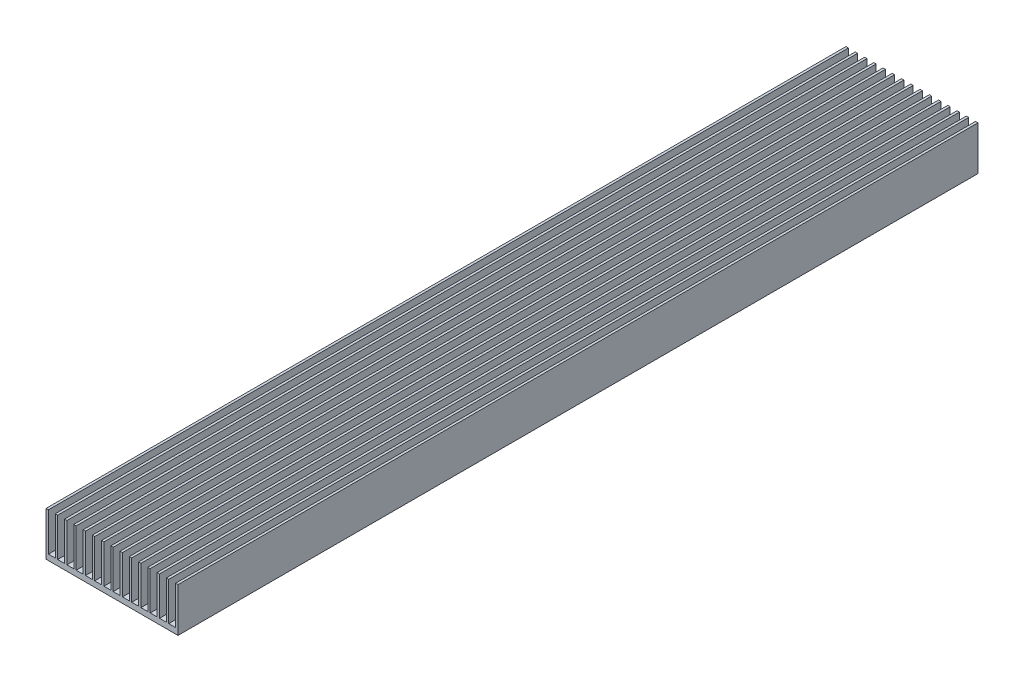
SolidWorks part; units mm, degrees
ref_plane "Ön Düzlem" through (0, 0, 0) normal (0, 0, 1) x (1, 0, 0)
ref_plane "Üst Düzlem" through (0, 0, 0) normal (0, 1, 0) x (1, 0, 0)
ref_plane "Sağ Düzlem" through (0, 0, 0) normal (1, 0, 0) x (0, 0, -1)
sketch "Sketch1" plane through (0, 0, 0) normal (0, 0, 1) x (1, 0, 0)
  line L0 (11.5714, 7) -> (11.5714, 55)
  line L1 (0, 0) -> (165, 0)
  line L2 (0, 0) -> (0, 7)
  line L3 (3, 7) -> (11.5714, 7)
  line L4 (165, 0) -> (165, 10)
  line L6 (0, 7) -> (0, 55)
  line L7 (0, 55) -> (3, 55)
  line L8 (3, 7) -> (3, 55)
  line L10 (14.5714, 7) -> (14.5714, 55)
  line L11 (11.5714, 55) -> (14.5714, 55)
  line L12 (23.1429, 7) -> (23.1429, 55)
  line L14 (26.1429, 7) -> (26.1429, 55)
  line L15 (23.1429, 55) -> (26.1429, 55)
  line L16 (34.7143, 7) -> (34.7143, 55)
  line L18 (37.7143, 7) -> (37.7143, 55)
  line L19 (34.7143, 55) -> (37.7143, 55)
  line L20 (46.2857, 7) -> (46.2857, 55)
  line L22 (49.2857, 7) -> (49.2857, 55)
  line L23 (46.2857, 55) -> (49.2857, 55)
  line L24 (57.8571, 7) -> (57.8571, 55)
  line L26 (60.8571, 7) -> (60.8571, 55)
  line L27 (57.8571, 55) -> (60.8571, 55)
  line L28 (69.4286, 7) -> (69.4286, 55)
  line L30 (72.4286, 7) -> (72.4286, 55)
  line L31 (69.4286, 55) -> (72.4286, 55)
  line L32 (81, 7) -> (81, 55)
  line L34 (84, 7) -> (84, 55)
  line L35 (81, 55) -> (84, 55)
  line L36 (92.5714, 7) -> (92.5714, 55)
  line L38 (95.5714, 7) -> (95.5714, 55)
  line L39 (92.5714, 55) -> (95.5714, 55)
  line L40 (104.1429, 7) -> (104.1429, 55)
  line L42 (107.1429, 7) -> (107.1429, 55)
  line L43 (104.1429, 55) -> (107.1429, 55)
  line L44 (115.7143, 7) -> (115.7143, 55)
  line L46 (118.7143, 7) -> (118.7143, 55)
  line L47 (115.7143, 55) -> (118.7143, 55)
  line L48 (127.2857, 7) -> (127.2857, 55)
  line L50 (130.2857, 7) -> (130.2857, 55)
  line L51 (127.2857, 55) -> (130.2857, 55)
  line L52 (138.8571, 7) -> (138.8571, 55)
  line L54 (141.8571, 7) -> (141.8571, 55)
  line L55 (138.8571, 55) -> (141.8571, 55)
  line L56 (150.4286, 7) -> (150.4286, 55)
  line L58 (153.4286, 7) -> (153.4286, 55)
  line L59 (150.4286, 55) -> (153.4286, 55)
  line L60 (162, 7) -> (162, 55)
  line L62 (165, 7) -> (165, 55)
  line L63 (162, 55) -> (165, 55)
  line L78 (14.5714, 7) -> (23.1429, 7)
  line L79 (26.1429, 7) -> (34.7143, 7)
  line L80 (37.7143, 7) -> (46.2857, 7)
  line L81 (49.2857, 7) -> (57.8571, 7)
  line L82 (60.8571, 7) -> (69.4286, 7)
  line L83 (72.4286, 7) -> (81, 7)
  line L84 (84, 7) -> (92.5714, 7)
  line L85 (95.5714, 7) -> (104.1429, 7)
  line L86 (107.1429, 7) -> (115.7143, 7)
  line L87 (118.7143, 7) -> (127.2857, 7)
  line L88 (130.2857, 7) -> (138.8571, 7)
  line L89 (141.8571, 7) -> (150.4286, 7)
  line L90 (153.4286, 7) -> (162, 7)
  dimension "D1" = 165
  dimension "D2" = 7
  dimension "D3" = 48
  dimension "D4" = 3
  dimension "D5" = 15
extrude "Boss-Extrude1" add sketch "Sketch1" along normal blind 1000 contours L90 L58 L59 L56 L89 L54 L55 L52 L88 L50 L51 L48 L87 L46 L47 L44 L86 L42 L43 L40 L85 L38 L39 L36 L84 L34 L35 L32 L83 L30 L31 L28 L82 L26 L27 L24 L81 L22 L23 L20 L80 L18 L19 L16 L79 L14 L15 L12 L78 L10 L11
